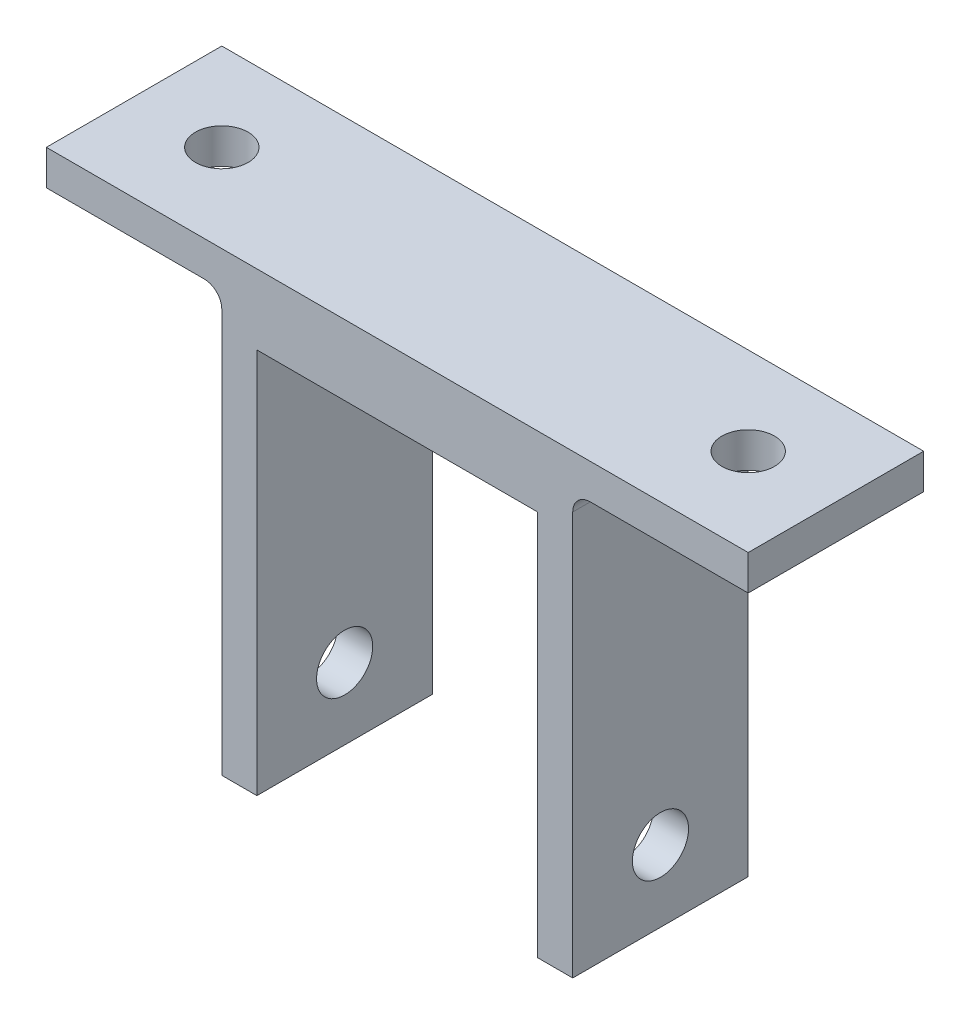
SolidWorks part; units mm, degrees
material "ABS"
ref_plane "Front Plane" through (0, 0, 0) normal (0, 0, 1) x (1, 0, 0)
ref_plane "Top Plane" through (0, 0, 0) normal (0, 1, 0) x (1, 0, 0)
ref_plane "Right Plane" through (0, 0, 0) normal (1, 0, 0) x (0, 0, -1)
sketch "Sketch1" plane through (0, 0, 0) normal (0, 0, 1) x (1, 0, 0)
  line L0 (-10, 10) -> (-10, -10)
  line L1 (-8, 8) -> (8, 8)
  line L2 (-8, 8) -> (-8, -8)
  line L4 (8, 8) -> (8, -8)
  line L5 (-8, 8) -> (8, -8) construction
  line L6 (-8, -8) -> (8, 8) construction
  line L8 (10, 10) -> (10, -10)
  line L9 (-10, 10) -> (10, 10)
  line L10 (-10, -10) -> (10, -10) construction
  line L11 (-8, -8) -> (8, -8) construction
  line L12 (-10, -10) -> (-10, -14)
  line L13 (10, -10) -> (10, -14)
  line L14 (-8, -8) -> (-8, -14)
  line L15 (-10, -14) -> (-8, -14)
  line L16 (8, -8) -> (8, -14)
  line L17 (8, -14) -> (10, -14)
  point P0 (0, 0)
  dimension "D1" = 16
  dimension "D2" = 16
  dimension "D4" = 4
  dimension "D3" = 2
extrude "Boss-Extrude1" add sketch "Sketch1" along normal blind 10
sketch "Sketch2" plane through (0, 10, 0) normal (0, 1, 0) x (1, 0, 0)
  line L0 (0, 7.0162) -> (0, -18.8908) construction
  line L1 (-20, 0) -> (20, 0)
  line L2 (-20, 0) -> (-20, -10)
  line L3 (-20, -10) -> (20, -10)
  line L4 (20, 0) -> (20, -10)
  circle A0 centre (-15, -5) radius 1.5
  circle A1 centre (15, -5) radius 1.5
  point P4 (0, 0)
  dimension "D5" = 3
  dimension "D1" = 10
  dimension "D2" = 40
  dimension "D3" = 5
  dimension "D4" = 5
extrude "Boss-Extrude2" add sketch "Sketch2" along normal blind 2
fillet "Fillet1" radius 1 2 edges at (10, 10, 5) (-10, 10, 5)
sketch "Sketch3" plane through (10, 0, 0) normal (1, 0, 0) x (0, 0, -1)
  circle A0 centre (-5, -9.9305) radius 1.6
  dimension "D1" = 3.2
extrude "Cut-Extrude1" cut sketch "Sketch3" against normal through all
